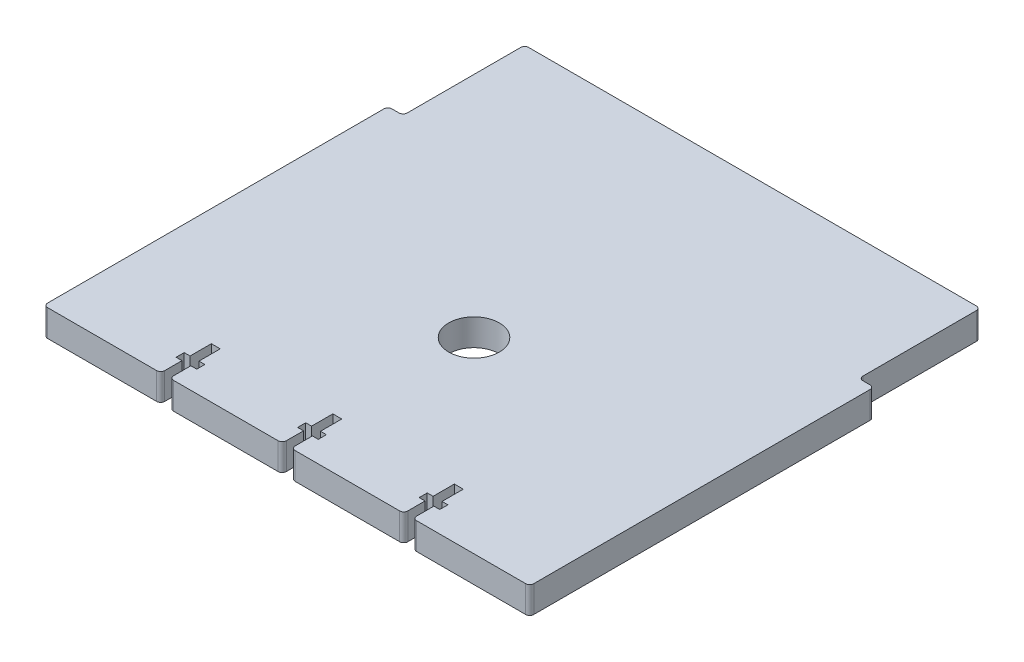
SolidWorks part; units mm, degrees
ref_plane "Front Plane" through (0, 0, 0) normal (0, 0, 1) x (1, 0, 0)
ref_plane "Top Plane" through (0, 0, 0) normal (0, 1, 0) x (1, 0, 0)
ref_plane "Right Plane" through (0, 0, 0) normal (1, 0, 0) x (0, 0, -1)
sketch "Sketch1" plane through (0, 0, 0) normal (0, 1, 0) x (1, 0, 0)
  line L1 (0, 0) -> (142.875, 0)
  line L2 (0, 107.95) -> (0, 146.05)
  line L3 (0, 146.05) -> (142.875, 146.05)
  line L4 (142.875, 107.95) -> (142.875, 146.05)
  line L5 (142.875, 0) -> (147.6375, 0)
  line L7 (142.875, 107.95) -> (147.6375, 107.95)
  line L8 (147.6375, 0) -> (147.6375, 107.95)
  line L9 (0, 0) -> (-4.7625, 0)
  line L11 (0, 107.95) -> (-4.7625, 107.95)
  line L12 (-4.7625, 0) -> (-4.7625, 107.95)
  dimension "D1" = 142.875
  dimension "D2" = 146.05
  dimension "D3" = 4.7625
  dimension "D4" = 4.7625
  dimension "D5" = 107.95
  dimension "D6" = 107.95
extrude "Boss-Extrude1" add sketch "Sketch1" along normal blind 8.382
sketch "Sketch10" plane through (0, 8.382, 0) normal (0, 1, 0) x (1, 0, 0)
  line L0 (71.4375, 146.05) -> (71.4375, 15.875) construction
  line L1 (70.0405, 9.2075) -> (68.199, 9.2075)
  line L2 (108.1405, 15.875) -> (110.9345, 15.875)
  line L3 (142.875, 146.05) -> (0, 146.05) construction
  line L4 (-4.7625, 0) -> (147.6375, 0) construction
  line L5 (70.0405, 6.6675) -> (70.0405, 0)
  line L6 (70.0405, 15.875) -> (72.8345, 15.875)
  line L7 (70.0405, 15.875) -> (70.0405, 9.2075)
  line L8 (70.0405, 0) -> (72.8345, 0)
  line L9 (72.8345, 15.875) -> (72.8345, 9.2075)
  line L10 (108.1405, 15.875) -> (108.1405, 9.2075)
  line L11 (110.9345, 15.875) -> (110.9345, 9.2075)
  line L12 (74.676, 6.6675) -> (72.8345, 6.6675)
  line L13 (74.676, 6.6675) -> (74.676, 9.2075)
  line L14 (74.676, 9.2075) -> (72.8345, 9.2075)
  line L15 (68.199, 6.6675) -> (68.199, 9.2075)
  line L16 (112.776, 9.2075) -> (110.9345, 9.2075)
  line L17 (112.776, 6.6675) -> (112.776, 9.2075)
  line L18 (70.0405, 6.6675) -> (68.199, 6.6675)
  line L19 (112.776, 6.6675) -> (110.9345, 6.6675)
  line L20 (110.9345, 6.6675) -> (110.9345, 0)
  line L21 (108.1405, 0) -> (110.9345, 0)
  line L22 (108.1405, 6.6675) -> (108.1405, 0)
  line L23 (108.1405, 6.6675) -> (106.299, 6.6675)
  line L24 (106.299, 6.6675) -> (106.299, 9.2075)
  line L25 (108.1405, 9.2075) -> (106.299, 9.2075)
  line L26 (72.8345, 6.6675) -> (72.8345, 0)
  line L27 (34.7345, 15.875) -> (34.7345, 9.2075)
  line L28 (31.9405, 15.875) -> (34.7345, 15.875)
  line L29 (31.9405, 15.875) -> (31.9405, 9.2075)
  line L30 (31.9405, 9.2075) -> (30.099, 9.2075)
  line L31 (30.099, 6.6675) -> (30.099, 9.2075)
  line L32 (31.9405, 6.6675) -> (30.099, 6.6675)
  line L33 (31.9405, 6.6675) -> (31.9405, 0)
  line L34 (34.7345, 6.6675) -> (34.7345, 0)
  line L35 (31.9405, 0) -> (34.7345, 0)
  line L36 (36.576, 6.6675) -> (34.7345, 6.6675)
  line L37 (36.576, 6.6675) -> (36.576, 9.2075)
  line L38 (36.576, 9.2075) -> (34.7345, 9.2075)
  point P6 (71.4375, 7.9375)
  point P11 (71.4375, 7.9375)
  dimension "D1" = 2.794
  dimension "D2" = 15.875
  dimension "D3" = 2.54
  dimension "D4" = 6.477
  dimension "D5" = 2
  dimension "D6" = 2
extrude "Cut-Extrude2" cut sketch "Sketch10" against normal through all
hole_wizard "5/8 (0.625) Diameter Hole1" positions "Sketch11" profile "Sketch13" hole size "5/8" standard "ANSI Inch" end condition through all
sketch "Sketch11" plane through (0, 0, 0) normal (0, -1, 0) x (-1, 0, 0)
  line L6 (0.127, 130.175) -> (-142.875, -12.7) construction
  point P26 (-71.4375, 58.7375)
sketch "Sketch13" plane through (71.4375, 0, -58.7375) normal (1, 0, 0) x (0, 0, -1)
  line L0 (0, 0) -> (0, 8.382)
  line L1 (0, 8.382) -> (7.9375, 8.382)
  line L2 (7.9375, 8.382) -> (7.9375, 0)
  line L5 (7.9375, 0) -> (0, 0)
  line L11 (0, -6.35) -> (0, 107.95) construction
  dimension "Thru Hole Dia." = 15.875
  dimension "Thru Hole Depth" = 8.382
fillet "Fillet1" radius 1.27 14 edges at (34.7345, 4.191, 0) (31.9405, 4.191, 0) (-4.7625, 4.191, 0) (-4.7625, 4.191, -107.95) (0, 4.191, -107.95) (0, 4.191, -146.05) (142.875, 4.191, -146.05) (142.875, 4.191, -107.95) (147.6375, 4.191, -107.95) (147.6375, 4.191, 0) (72.8345, 4.191, 0) (70.0405, 4.191, 0) (110.9345, 4.191, 0) (108.1405, 4.191, 0)
